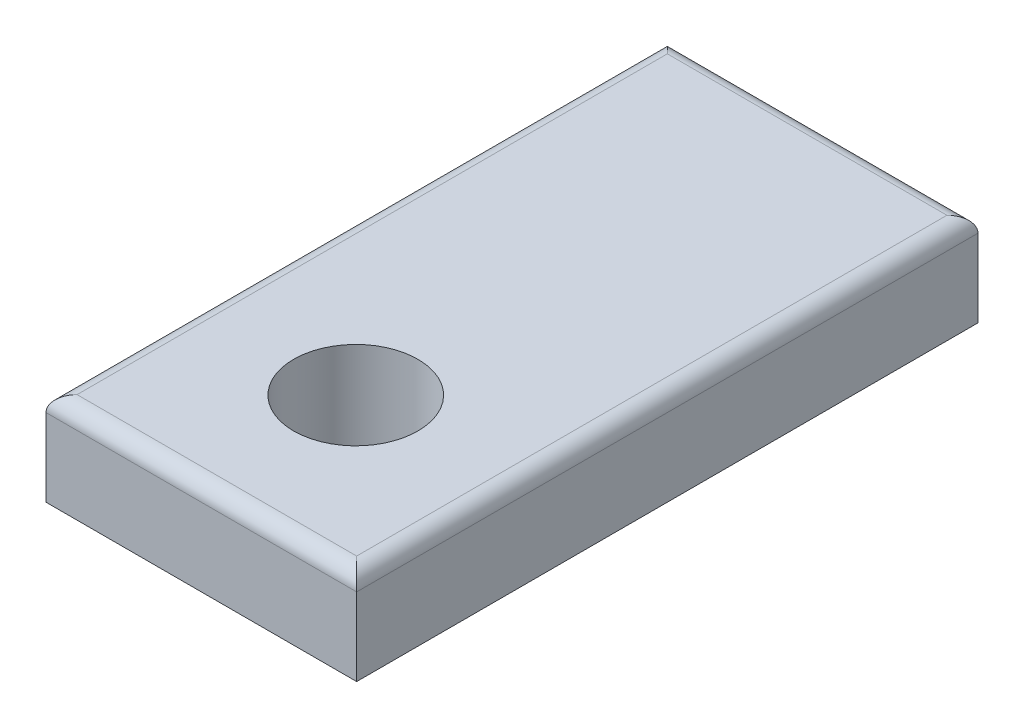
SolidWorks part; units mm, degrees
ref_plane "Front Plane" through (0, 0, 0) normal (0, 0, 1) x (1, 0, 0)
ref_plane "Top Plane" through (0, 0, 0) normal (0, 1, 0) x (1, 0, 0)
ref_plane "Right Plane" through (0, 0, 0) normal (1, 0, 0) x (0, 0, -1)
sketch "Sketch1" plane through (0, 0, 0) normal (0, 1, 0) x (1, 0, 0)
  line L1 (-5, -10) -> (5, -10)
  line L2 (-5, -10) -> (-5, 10)
  line L3 (-5, 10) -> (5, 10)
  line L4 (5, -10) -> (5, 10)
  line L5 (-5, -10) -> (5, 10) construction
  line L6 (-5, 10) -> (5, -10) construction
  point P0 (0, 0)
extrude "Boss-Extrude1" add sketch "Sketch1" along normal blind 3
sketch "Sketch2" plane through (0, 3, 0) normal (0, 1, 0) x (1, 0, 0)
  circle A0 centre (0, -5.0289) radius 2
extrude "Cut-Extrude1" cut sketch "Sketch2" against normal blind 3
sketch "Sketch3" plane through (0, 0, -10) normal (0, 0, -1) x (-1, 0, 0)
  line L0 (-5, 1.5) -> (5, 1.5)
  line L1 (-5, 3) -> (-5, 0) construction
  line L2 (5, 3) -> (5, 0) construction
fillet "Fillet1" radius 0.5 4 edges at (0, 3, 10) (-5, 3, 0) (0, 3, -10) (5, 3, 0)
